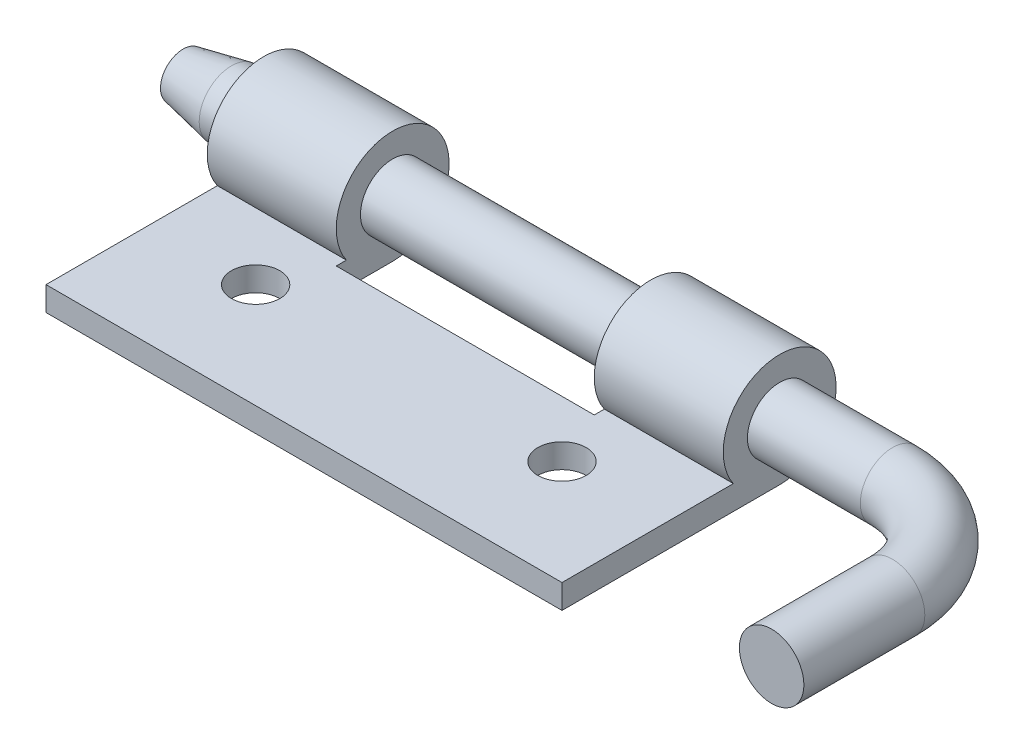
SolidWorks part; units mm, degrees
ref_plane "前视基准面" through (0, 0, 0) normal (0, 0, 1) x (1, 0, 0)
ref_plane "上视基准面" through (0, 0, 0) normal (0, 1, 0) x (1, 0, 0)
ref_plane "右视基准面" through (0, 0, 0) normal (1, 0, 0) x (0, 0, -1)
other "Configuration Table"
sketch "草图6" plane through (0, 0, 0) normal (1, 0, 0) x (0, 0, -1)
  circle A0 centre (0, 0) radius 3.5
  dimension "D1" = 7
extrude "凸台-拉伸4" add sketch "草图6" along normal blind 8
sketch "草图7" plane through (0, 0, 0) normal (-1, 0, 0) x (0, 0, 1)
  circle A0 centre (0, 0) radius 3.5 construction
  circle A1 centre (0, 0) radius 3.5
extrude "凸台-拉伸5" add sketch "草图7" against normal blind 8 from offset 24 separate body offset against normal yes
sketch "草图8" plane through (0, 0, 0) normal (0, 1, 0) x (1, 0, 0)
  line L0 (32, 3.5) -> (24, 3.5) construction
  line L1 (0, 0) -> (8, 0)
  line L2 (0, 0) -> (0, -13.5)
  line L3 (0, -13.5) -> (32, -13.5)
  line L4 (32, 0) -> (32, -13.5)
  line L5 (8, 0) -> (8, -3.5)
  line L6 (8, -3.5) -> (8, 3.5) construction
  line L7 (8, -3.5) -> (24, -3.5)
  line L8 (24, -3.5) -> (24, 0)
  line L9 (24, 3.5) -> (24, -3.5) construction
  line L10 (24, -3.5) -> (32, -3.5) construction
  line L11 (24, 0) -> (32, 0)
  circle A0 centre (25.5, -7) radius 1.5
  circle A1 centre (6.5, -7) radius 1.5
  point P9 (25.5, -8.5)
  point P10 (27, -7)
  dimension "D5" = 3
  dimension "D6" = 3
  dimension "D1" = 32
  dimension "D2" = 17
  dimension "D3" = 5
  dimension "D4" = 5
  dimension "D7" = 19
extrude "凸台-拉伸6" add sketch "草图8" along normal blind 1.5 from offset 3.5 offset against normal yes
sketch "草图9" plane through (0, 0, 0) normal (0, 1, 0) x (1, 0, 0)
  line L0 (-5, 0) -> (39, 0)
  line L1 (45, -6) -> (45, -13.5)
  line L2 (0, -13.5) -> (32, -13.5) construction
  line L3 (0, -3.85) -> (0, 3.85) construction
  arc A0 (39, 0) -> (45, -6) centre (39, -6) cw
  point P5 (0, 0)
  point P9 (0, 0)
  point P12 (0, 0)
  point P14 (0, 0)
  point P16 (38, -13.5)
  point P17 (32, -6)
  point P18 (0, 0)
  dimension "D3" = 6
  dimension "D1" = 5
  dimension "D2" = 50
ref_plane "基准面1" through (-5, 0, 0) normal (1, 0, 0) x (0, 0, -1)
sketch "草图10" plane through (-5, 0, 0) normal (1, 0, 0) x (0, 0, -1)
  circle A0 centre (0, 0) radius 2
  dimension "D1" = 4
sweep "扫描1" add profiles "草图10" path "草图9"
sketch "草图11" plane through (0, 0, 0) normal (0, 1, 0) x (1, 0, 0)
  line L0 (-14.9229, 0) -> (-4.4953, 0)
  line L1 (-3.85, 0) -> (3.85, 0) construction
  line L2 (-5, -1.4) -> (-5, 1.4)
  line L3 (-5, -55) -> (-5, 55) construction
  line L4 (-5, 1.4) -> (-2, 2)
  line L5 (0, 2) -> (-5, 2) construction
  line L6 (-2, 2) -> (-2, -2)
  line L7 (-5, -1.4) -> (-2, -2)
  line L8 (-2, 2) -> (-5, 2)
  line L9 (-5, 2) -> (-5, 1.4)
  point P14 (-2, 0)
  point P15 (-5, 0)
  dimension "D1" = 2.8
  dimension "D2" = 3
revolve "切除-旋转1" cut sketch "草图11" angle 360 about L0
